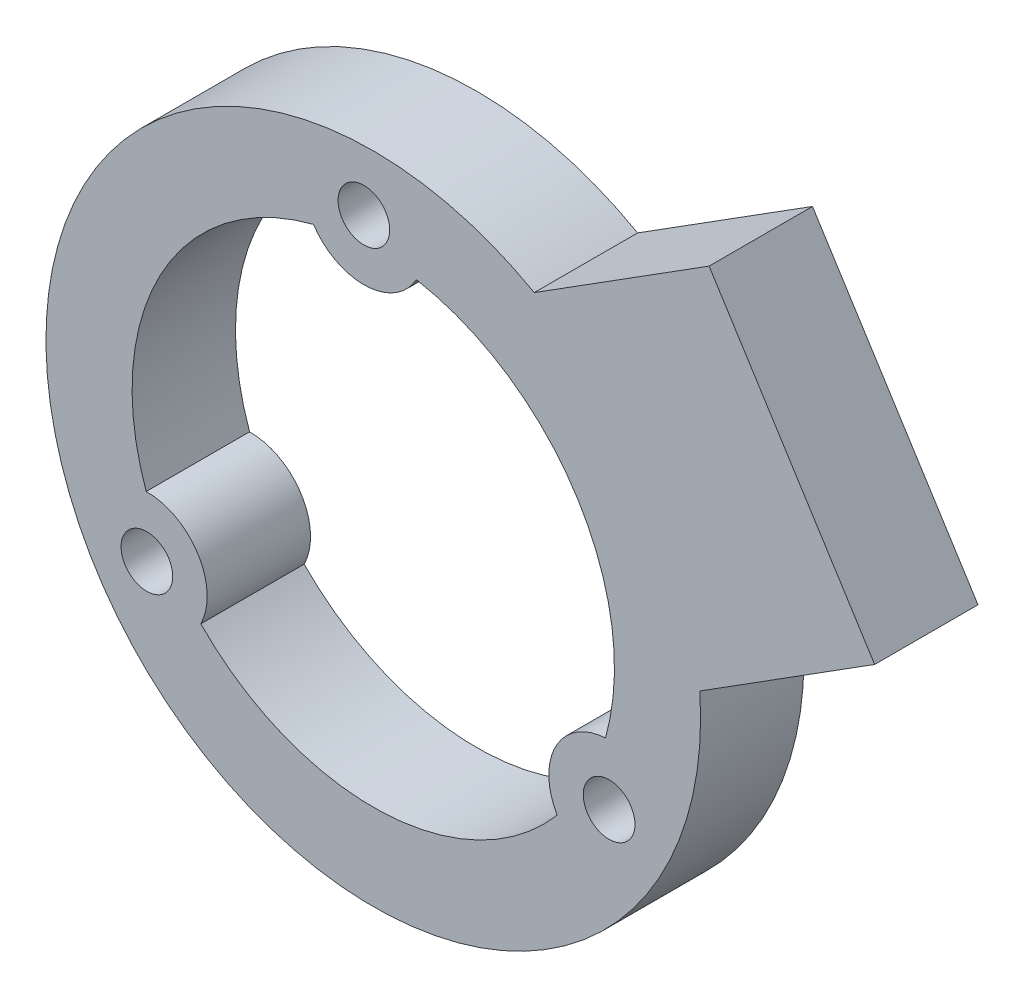
SolidWorks part; units mm, degrees
ref_plane "Plan de face" through (0, 0, 0) normal (0, 0, 1) x (1, 0, 0)
ref_plane "Plan de dessus" through (0, 0, 0) normal (0, 1, 0) x (1, 0, 0)
ref_plane "Plan de droite" through (0, 0, 0) normal (1, 0, 0) x (0, 0, -1)
sketch "Esquisse1" plane through (0, 0, 0) normal (0, 0, 1) x (1, 0, 0)
  line L0 (-0.5467, 15.4904) -> (-13.1417, -8.2186) construction
  line L1 (-13.1417, -8.2186) -> (13.6884, -7.2717) construction
  line L2 (13.6884, -7.2717) -> (-0.5467, 15.4904) construction
  line L3 (29.1009, 7.7271) -> (19.4925, 22.9481)
  line L5 (29.1009, 7.7271) -> (18.954, 1.3208)
  line L7 (19.4925, 22.9481) -> (9.3448, 16.5431)
  arc A0 (9.3448, 16.5431) -> (18.954, 1.3208) centre (0, 0) ccw
  circle A2 centre (-0.5467, 15.4904) radius 1.5
  circle A3 centre (-13.1417, -8.2186) radius 1.5
  circle A4 centre (13.6884, -7.2717) radius 1.5
  arc A5 (-3.4686, 13.5635) -> (2.5037, 13.7743) centre (-0.5467, 15.4904) ccw
  arc A6 (-10.0121, -9.7856) -> (-13.1808, -4.7189) centre (-13.1417, -8.2186) ccw
  arc A7 (13.4806, -3.7779) -> (10.677, -9.0554) centre (13.6884, -7.2717) ccw
  arc A8 (-10.0121, -9.7856) -> (10.677, -9.0554) centre (0, 0) ccw
  arc A9 (-3.4686, 13.5635) -> (-13.1808, -4.7189) centre (0, 0) ccw
  arc A10 (13.4806, -3.7779) -> (2.5037, 13.7743) centre (0, 0) ccw
  dimension "D1" = 38
  dimension "D2" = 18
  dimension "D3" = 3
  dimension "D4" = 3
  dimension "D5" = 3
  dimension "D8" = 15.5
  dimension "D9" = 15.5
  dimension "D10" = 15.5
  dimension "D11" = 7
  dimension "D12" = 7
  dimension "D13" = 7
  dimension "D6" = 60
  dimension "D7" = 60
  dimension "D14" = 90.004
  dimension "D15" = 12
  dimension "D16" = 90.004
  dimension "D17" = 12
extrude "Boss.-Extru.3" add sketch "Esquisse1" along normal blind 6
